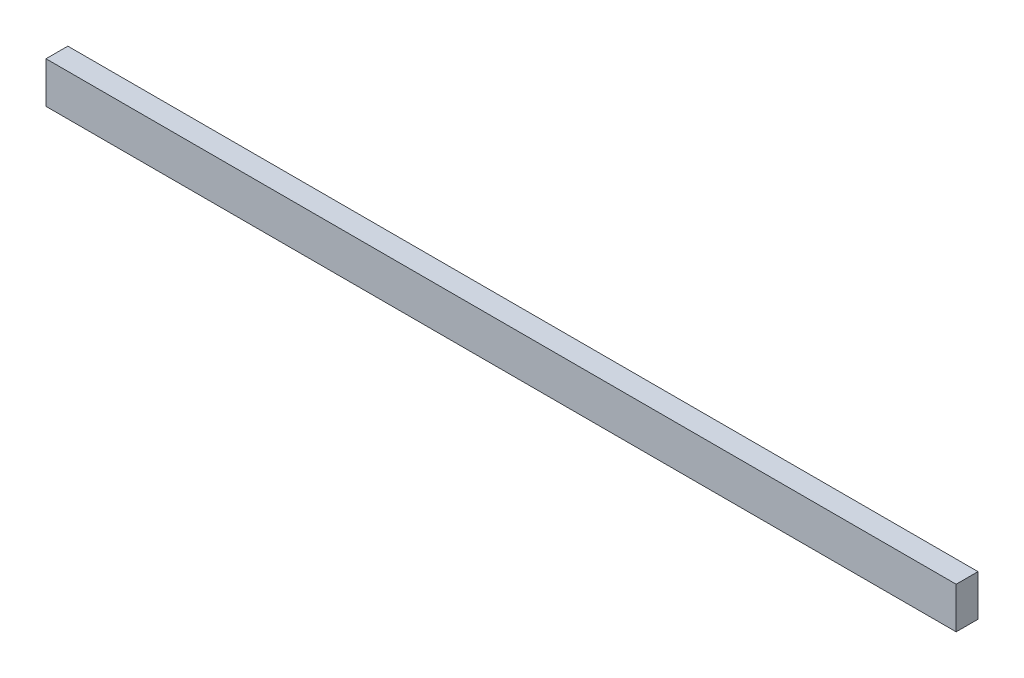
SolidWorks part; units mm, degrees
ref_plane "Front Plane" through (0, 0, 0) normal (0, 0, 1) x (1, 0, 0)
ref_plane "Top Plane" through (0, 0, 0) normal (0, 1, 0) x (1, 0, 0)
ref_plane "Right Plane" through (0, 0, 0) normal (1, 0, 0) x (0, 0, -1)
sketch "Sketch1" plane through (0, 0, 0) normal (0, 0, 1) x (1, 0, 0)
  line L1 (-375, -17) -> (375, -17)
  line L2 (-375, -17) -> (-375, 17)
  line L3 (-375, 17) -> (375, 17)
  line L4 (375, -17) -> (375, 17)
  line L5 (-375, -17) -> (375, 17) construction
  line L6 (-375, 17) -> (375, -17) construction
  point P0 (0, 0)
  dimension "D1" = 750
  dimension "D2" = 34
extrude "Boss-Extrude1" add sketch "Sketch1" along normal blind 18
